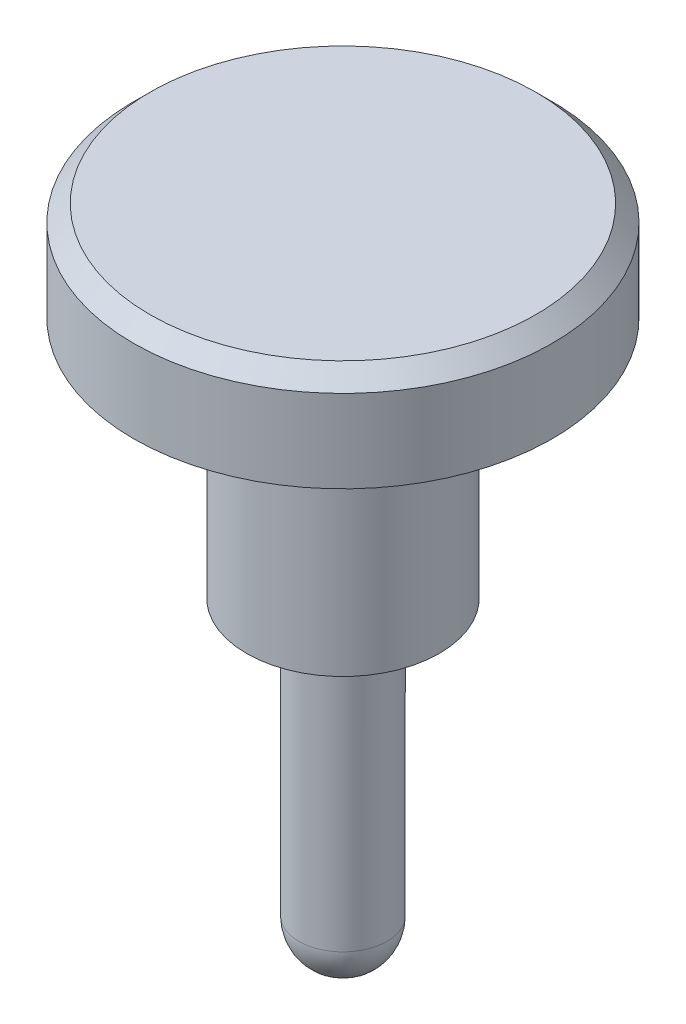
SolidWorks part; units mm, degrees
ref_plane "Front Plane" through (0, 0, 0) normal (0, 0, 1) x (1, 0, 0)
ref_plane "Top Plane" through (0, 0, 0) normal (0, 1, 0) x (1, 0, 0)
ref_plane "Right Plane" through (0, 0, 0) normal (1, 0, 0) x (0, 0, -1)
sketch "Sketch1" plane through (0, 0, 0) normal (0, 0, 1) x (1, 0, 0)
  line L0 (0, 18) -> (35, 18)
  line L1 (35, 18) -> (38, 15)
  line L2 (38, 15) -> (38, 0)
  line L3 (38, 0) -> (0, 0)
  line L4 (0, 0) -> (0, 18)
  line L5 (17.5, 0) -> (17.5, -44)
  line L6 (17.5, -44) -> (0, -44)
  line L7 (0, -44) -> (0, 0)
  line L8 (0, -94) -> (0, -44)
  line L9 (0, -94) -> (8, -94)
  line L10 (8, -94) -> (8, -44)
  line L11 (38, 15) -> (0, 15)
  line L12 (0, -94) -> (0, -102)
  line L13 (0, 67.7179) -> (0, -147.3984) construction
  arc A0 (8, -94) -> (0, -102) centre (0, -94) cw
  dimension "D9" = 8
  dimension "D1" = 35
  dimension "D2" = 3
  dimension "D3" = 45
  dimension "D4" = 112
  dimension "D5" = 44
  dimension "D6" = 17.5
  dimension "D7" = 50
  dimension "D8" = 8
revolve "Revolve1" add sketch "Sketch1" angle 360 about L13
